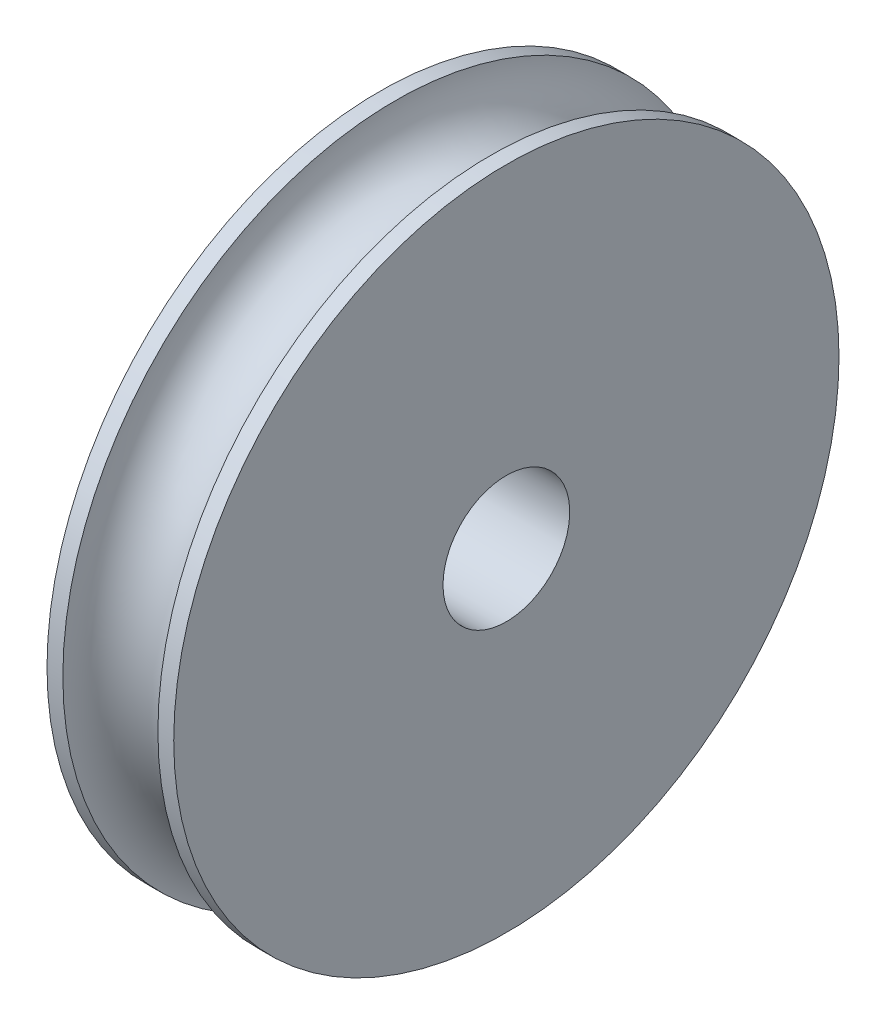
SolidWorks part; units mm, degrees
ref_plane "Front Plane" through (0, 0, 0) normal (0, 0, 1) x (1, 0, 0)
ref_plane "Top Plane" through (0, 0, 0) normal (0, 1, 0) x (1, 0, 0)
ref_plane "Right Plane" through (0, 0, 0) normal (1, 0, 0) x (0, 0, -1)
sketch "Sketch1" plane through (0, 0, 0) normal (0, 1, 0) x (1, 0, 0)
  line L0 (0, -1) -> (2, -1)
  line L1 (2, -1) -> (2, -5.25)
  line L3 (0, -5.25) -> (0, -1)
  line L4 (0, -5.25) -> (0.25, -5.25)
  line L5 (2, -5.25) -> (1.75, -5.25)
  line L6 (0, 0) -> (6.609, 0) construction
  arc A0 (0.25, -5.25) -> (1.75, -5.25) centre (1, -5.25) cw
  dimension "D1" = 1
  dimension "D2" = 2
  dimension "D3" = 4.25
  dimension "D4" = 0.25
revolve "Revolve1" add sketch "Sketch1" angle 360 about L6
ref_plane "Plane1" through (1, 0, 0) normal (1, 0, 0) x (0, 0, -1)
sketch "Sketch2" plane through (1, 0, 0) normal (1, 0, 0) x (0, 0, -1)
  circle A0 centre (0, 0) radius 5.25 construction
